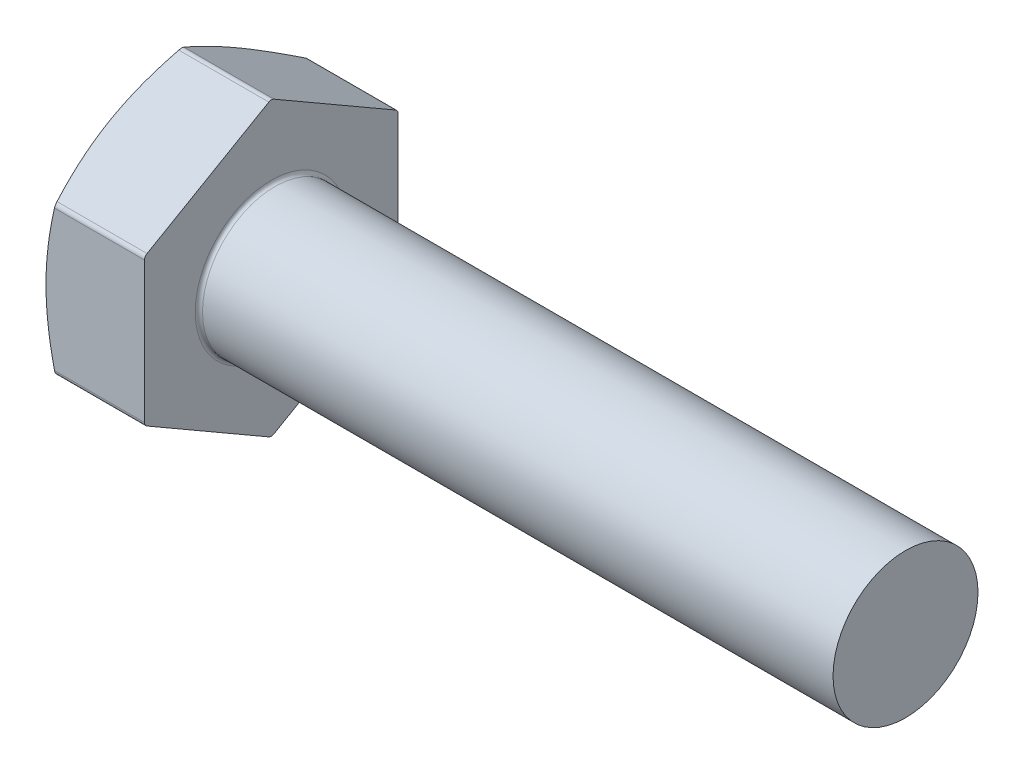
SolidWorks part; units mm, degrees
ref_plane "Front Plane" through (0, 0, 0) normal (0, 0, 1) x (1, 0, 0)
ref_plane "Top Plane" through (0, 0, 0) normal (0, 1, 0) x (1, 0, 0)
ref_plane "Right Plane" through (0, 0, 0) normal (1, 0, 0) x (0, 0, -1)
sketch "Sketch1" plane through (0, 0, 0) normal (0, 0, 1) x (1, 0, 0)
  line L0 (0, 0) -> (60, 0) construction
  line L1 (0, 0) -> (-2.8, 0) construction
  line L2 (0, 3.5) -> (0, -3.5) construction
  line L3 (-2.8, 3.5) -> (-2.8, -3.5) construction
  line L4 (60, 2) -> (60, -2) construction
  line L5 (-2.8, -3.83) -> (-2.8, 3.83)
  line L8 (59.3, 2) -> (60, 2) construction
  point P8 (59.3, 0)
  point P11 (57.55, -2)
  point P12 (2.1, 0)
  point P13 (5.95, 0)
  point P16 (-2.8, 0)
  point P17 (56.15, 0)
  dimension "Head Height" = 2.8
  dimension "Head Width" = 7
  dimension "Length" = 60
  dimension "Thread Size" = 4
  dimension "D1" = 2.45
  dimension "Thread Pitch" = 0.7
  dimension "a" = 2.1
  dimension "e" = 7.66
  dimension "D3" = 3.85
  dimension "D2" = 3.85
sketch "Sketch2" plane through (0, 0, 0) normal (1, 0, 0) x (0, 0, -1)
  circle A0 centre (0, 0) radius 2
extrude "Boss-Extrude1" add sketch "Sketch2" along normal up to vertex (60 mm away) up to point (60, 2, 0)
sketch "Sketch3" plane through (0, 0, 0) normal (-1, 0, 0) x (0, 0, 1)
  line L0 (0, 4.0415) -> (0, 0) construction
  line L1 (0, 4.0415) -> (-3.5, 2.0207)
  line L2 (-3.5, 2.0207) -> (-3.5, -2.0207)
  line L3 (-3.5, -2.0207) -> (0, -4.0415)
  line L4 (0, -4.0415) -> (3.5, -2.0207)
  line L5 (3.5, -2.0207) -> (3.5, 2.0207)
  line L6 (3.5, 2.0207) -> (0, 4.0415)
  circle A0 centre (0, 0) radius 3.5 construction
extrude "Boss-Extrude2" add sketch "Sketch3" along normal up to vertex (2.8 mm away) up to point (-2.8, 3.5, 0)
sketch "Sketch5" plane through (-2.8, 0, 0) normal (-1, 0, 0) x (0, 0, 1)
  circle A0 centre (0, 0) radius 3.5 construction
  circle A1 centre (0, 0) radius 3.5 construction
  circle A2 centre (0, 0) radius 3.325
  dimension "D1" = 0.175
extrude "Cut-Extrude1" cut sketch "Sketch5" against normal up to vertex (2.8 mm away) draft 65 flip side to cut up to point (0, 0, 0)
fillet "Fillet7" radius 0.14 6 edges at (-1.233, -4.0415, 0) (-1.233, -2.0207, -3.5) (-1.233, 2.0207, -3.5) (-1.233, 4.0415, 0) (-1.233, -2.0207, 3.5) (-1.233, 2.0207, 3.5)
chamfer "Chamfer1" distance 0.525 angle 45 1 edges at (60, 0, -2)
fillet "Fillet4" radius 0.1 1 edges at (0, 0, 2)
sketch "Reference Sketch1" plane through (0, 0, 0) normal (1, 0, 0) x (0, 0, -1)
  line L1 (0, 4.0415) -> (-3.5, 2.0207)
  line L2 (-3.5, 2.0207) -> (-3.5, -2.0207)
  line L3 (-3.5, -2.0207) -> (0, -4.0415)
  line L4 (0, -4.0415) -> (3.5, -2.0207)
  line L5 (3.5, -2.0207) -> (3.5, 2.0207)
  line L6 (3.5, 2.0207) -> (0, 4.0415)
  circle A0 centre (0, 0) radius 3.5 construction
  circle A1 centre (0, 0) radius 3.5
sketch "Sketch6" plane through (60, 0, 0) normal (1, 0, 0) x (0, 0, -1)
  circle A0 centre (0, 0) radius 2
  circle A1 centre (0, 0) radius 2 construction
extrude "Cut-Extrude2" cut sketch "Sketch6" against normal blind 42.5
equation "\"D1@Chamfer1\"=\"Thread Pitch@Sketch1\"*0.750"
equation "\"D1@Sketch1\"=\"Thread Pitch@Sketch1\"*3.5"
equation "\"D1@Sketch5\"=\"Head Width@Sketch1\"*0.025"
equation "\"D1@Fillet4\"=\"Thread Size@Sketch1\"*0.025"
equation "\"D1@Fillet7\"=\"Head Width@Sketch1\"*0.02"
equation "\"D3@Sketch1\"=\"D2@Sketch1\""
equation "\"D2@Sketch1\"=\"D1@Sketch1\"+(\"Thread Pitch@Sketch1\"*2)"
